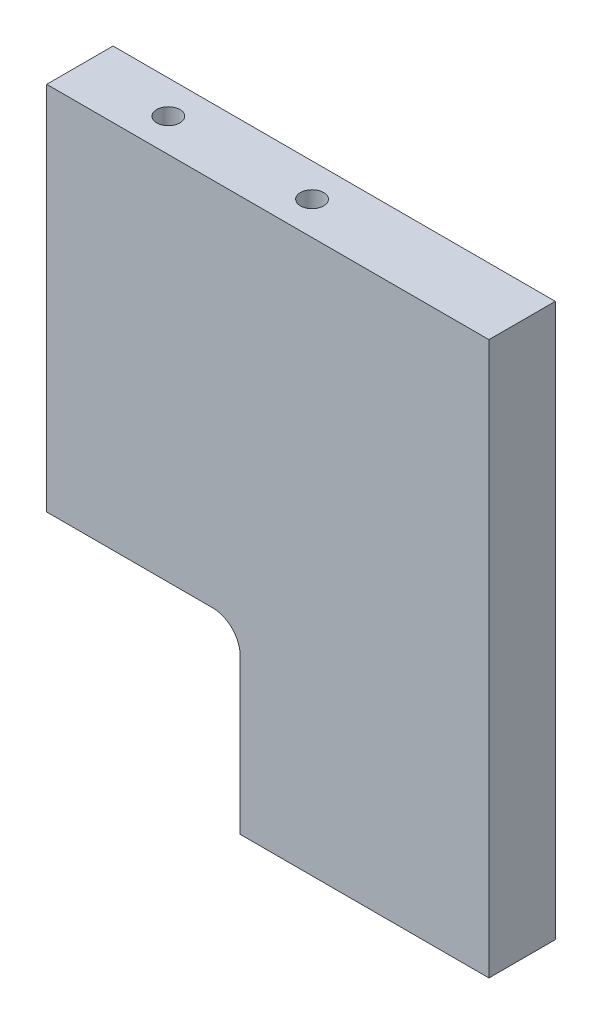
SolidWorks part; units mm, degrees
material "SKD11淬火HRC56-60"
ref_plane "前基準面" through (0, 0, 0) normal (0, 0, 1) x (1, 0, 0)
ref_plane "上基準面" through (0, 0, 0) normal (0, 1, 0) x (1, 0, 0)
ref_plane "右基準面" through (0, 0, 0) normal (1, 0, 0) x (0, 0, -1)
sketch "草图1" plane through (0, 0, 0) normal (0, 0, 1) x (1, 0, 0)
  line L0 (0, 0) -> (-45, 0)
  line L1 (-45, 0) -> (-45, 33)
  line L2 (-45, 33) -> (-80, 33)
  line L3 (-80, 33) -> (-80, 100)
  line L4 (-80, 100) -> (0, 100)
  line L7 (0, 100) -> (0, 0)
  dimension "D1" = 80
  dimension "D2" = 45
  dimension "D4" = 33
  dimension "D5" = 100
extrude "凸台-拉伸1" add sketch "草图1" along normal blind 12
fillet "圆角1" radius 5 1 edges at (-45, 33, 6)
hole_wizard "M5 螺纹孔1" positions "草图3" profile "草图2" tap size "M5" standard "ISO"
sketch "草图3" plane through (0, 0, 0) normal (0, -1, 0) x (1, 0, 0)
  point P0 (-6, 6)
  point P1 (-21, 6)
sketch "草图2" plane through (-6, 0, 6) normal (1, 0, 0) x (0, 0, -1)
  line L0 (0, 0) -> (0, 13.6618)
  line L1 (0, 13.6618) -> (2.1, 12.4)
  line L2 (2.1, 12.4) -> (2.1, 0)
  line L5 (2.1, 0) -> (0, 0)
  line L10 (0, 13.6618) -> (-2.1, 12.4) construction
  line L11 (0, -6.35) -> (0, 107.95) construction
  dimension "螺纹孔钻头直径" = 4.2
  dimension "螺纹孔钻头深度" = 12.4
  dimension "导头角度" = 118
cosmetic thread "孔螺蚊线1" parameters "D1"=10, "D2"=5
cosmetic thread "孔螺蚊线2" parameters "D1"=10, "D2"=5
hole_wizard "M5 螺纹孔2" positions "草图5" profile "草图4" tap size "M5" standard "ISO"
sketch "草图5" plane through (0, 100, 0) normal (0, 1, 0) x (-1, 0, 0)
  point P0 (38, 6)
  point P1 (64, 6)
sketch "草图4" plane through (-38, 100, 6) normal (1, 0, 0) x (0, 0, 1)
  line L0 (0, 0) -> (0, 13.6618)
  line L1 (0, 13.6618) -> (2.1, 12.4)
  line L2 (2.1, 12.4) -> (2.1, 0)
  line L5 (2.1, 0) -> (0, 0)
  line L10 (0, 13.6618) -> (-2.1, 12.4) construction
  line L11 (0, -6.35) -> (0, 107.95) construction
  dimension "螺纹孔钻头直径" = 4.2
  dimension "螺纹孔钻头深度" = 12.4
  dimension "导头角度" = 118
cosmetic thread "孔螺蚊线3" parameters "D1"=10, "D2"=5
cosmetic thread "孔螺蚊线4" parameters "D1"=10, "D2"=5
